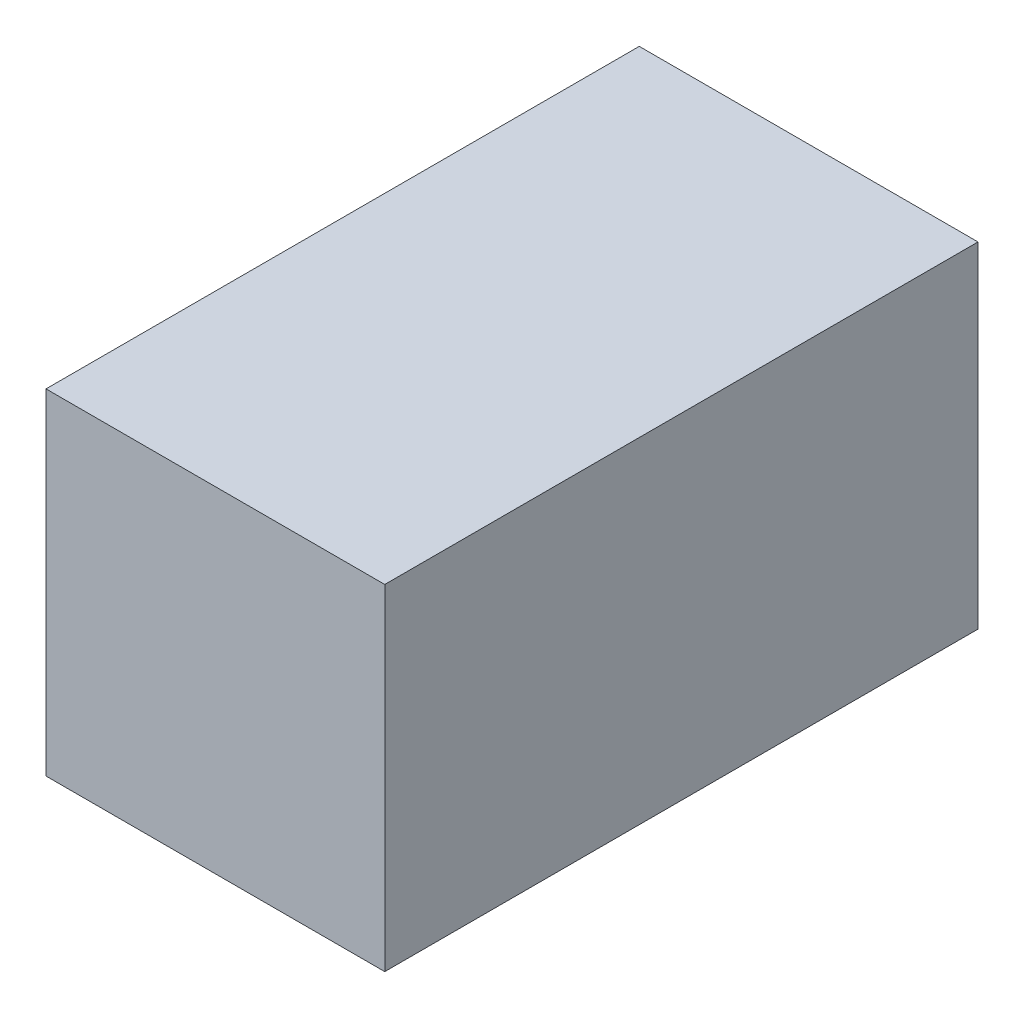
SolidWorks part; units mm, degrees
ref_plane "Front Plane" through (0, 0, 0) normal (0, 0, 1) x (1, 0, 0)
ref_plane "Top Plane" through (0, 0, 0) normal (0, 1, 0) x (1, 0, 0)
ref_plane "Right Plane" through (0, 0, 0) normal (1, 0, 0) x (0, 0, -1)
sketch "Sketch1" plane through (0, 0, 0) normal (0, 0, 1) x (1, 0, 0)
  line L0 (7.4676, -4.9022) -> (-2.54, -4.9022)
  line L1 (-2.54, -4.9022) -> (-2.54, 5.0038)
  line L2 (-2.54, 5.0038) -> (7.4676, 5.0038)
  line L3 (7.4676, 5.0038) -> (7.4676, -4.9022)
extrude "Component_Outline" add sketch "Sketch1" along normal blind 17.526 separate body
sketch3d "3DSketch1"
  line L0 (0, 0, 0) -> (1, 0, 0)
  line L1 (0, 0, 0) -> (0, 1, 0)
  line L2 (0, 0, 0) -> (0, 0, 1)
  point P0 (0, 0, 0)
